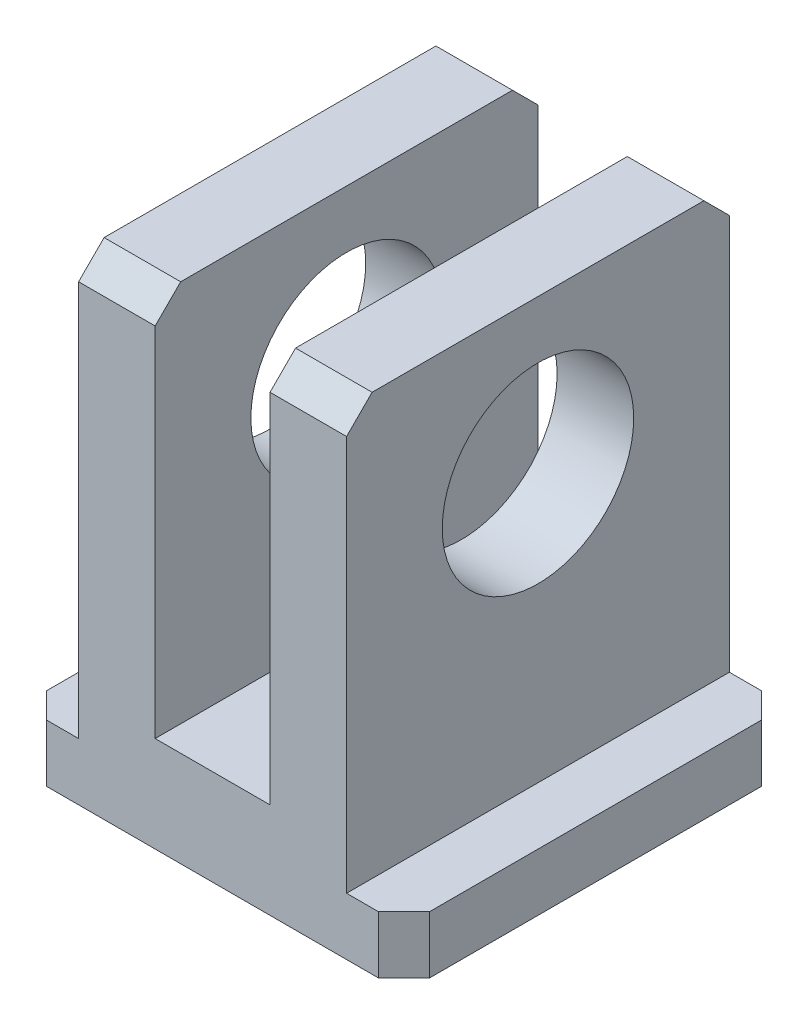
SolidWorks part; units mm, degrees
ref_plane "前视基准面" through (0, 0, 0) normal (0, 0, 1) x (1, 0, 0)
ref_plane "上视基准面" through (0, 0, 0) normal (0, 1, 0) x (1, 0, 0)
ref_plane "右视基准面" through (0, 0, 0) normal (1, 0, 0) x (0, 0, -1)
other "Configuration Table"
sketch "草图1" plane through (0, 0, 0) normal (0, 1, 0) x (1, 0, 0)
  line L0 (13, 15) -> (15, 13)
  line L1 (-13, -15) -> (13, -15)
  line L2 (-15, -13) -> (-15, 13)
  line L3 (-13, 15) -> (13, 15)
  line L4 (15, -13) -> (15, 13)
  line L5 (0, 15) -> (0, -15) construction
  line L6 (-15, 0) -> (15, 0) construction
  line L7 (-15, 13) -> (-13, 15)
  line L8 (-15, -13) -> (-13, -15)
  line L9 (13, -15) -> (15, -13)
  point P0 (0, 0)
  point P1 (15, 15)
  point P2 (-15, -15)
  point P3 (-15, 15)
  point P768 (15, -15)
extrude "凸台-拉伸1" add sketch "草图1" along normal blind 4.5
sketch "草图2" plane through (0, 4.5, 0) normal (0, 1, 0) x (1, 0, 0)
  line L0 (-10.5, 15) -> (-10.5, -15)
  line L1 (13, 15) -> (-13, 15) construction
  line L2 (-13, -15) -> (13, -15) construction
  line L3 (0, 15) -> (0, -15) construction
  line L4 (10.5, 15) -> (10.5, -15)
  line L5 (-10.5, 15) -> (10.5, 15)
  line L6 (-10.5, -15) -> (10.5, -15)
  dimension "D1" = 21
extrude "凸台-拉伸2" add sketch "草图2" along normal blind 3
sketch "草图3" plane through (0, 7.5, 0) normal (0, 1, 0) x (1, 0, 0)
  line L0 (-4.5, 15) -> (-4.5, -15)
  line L1 (10.5, 15) -> (-10.5, 15) construction
  line L2 (-10.5, -15) -> (10.5, -15) construction
  line L3 (0, 15) -> (0, -15) construction
  line L4 (-4.5, -15) -> (-10.5, -15)
  line L5 (-10.5, -15) -> (-10.5, 15)
  line L6 (-10.5, 15) -> (-4.5, 15)
  line L7 (4.5, -15) -> (10.5, -15)
  line L8 (10.5, 15) -> (4.5, 15)
  line L9 (4.5, 15) -> (4.5, -15)
  line L10 (10.5, -15) -> (10.5, 15)
  dimension "D1" = 9
extrude "凸台-拉伸3" add sketch "草图3" along normal blind 30
sketch "草图4" plane through (10.5, 0, 0) normal (1, 0, 0) x (0, 0, -1)
  line L0 (-13, 37.5) -> (-15, 35.5)
  line L1 (-15, 37.5) -> (15, 37.5) construction
  line L2 (-15, 37.5) -> (-15, 4.5) construction
  line L3 (-15, 35.5) -> (-15, 37.5)
  line L4 (-15, 37.5) -> (-13, 37.5)
  line L5 (0, 37.5) -> (0, 0) construction
  line L6 (15, 37.5) -> (13, 37.5)
  line L7 (15, 35.5) -> (15, 37.5)
  line L8 (13, 37.5) -> (15, 35.5)
  circle A0 centre (0, 25.5) radius 7.5
  point P16 (0, 25.5)
  dimension "D2" = 15
  dimension "D1" = 2
  dimension "D3" = 25.5
sketch "草图5" plane through (10.5, 0, 0) normal (1, 0, 0) x (0, 0, -1)
extrude "切除-拉伸1" cut sketch "草图4" against normal blind 30 and the other way blind 30
